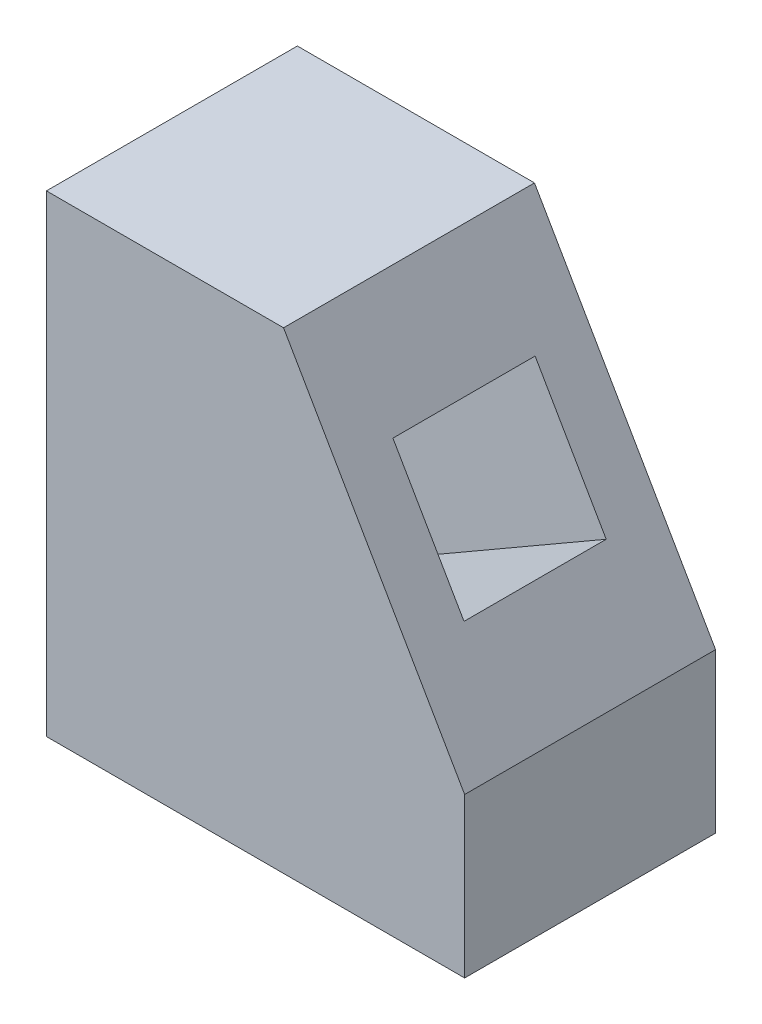
SolidWorks part; units mm, degrees
ref_plane "前视基准面" through (0, 0, 0) normal (0, 0, 1) x (1, 0, 0)
ref_plane "上视基准面" through (0, 0, 0) normal (0, 1, 0) x (1, 0, 0)
ref_plane "右视基准面" through (0, 0, 0) normal (1, 0, 0) x (0, 0, -1)
other "Configuration Table"
sketch "草图1" plane through (0, 0, 0) normal (0, 1, 0) x (1, 0, 0)
  line L0 (5, 0) -> (5, 6) construction
  line L1 (0, 0) -> (10, 0)
  line L2 (0, 0) -> (0, 6)
  line L3 (0, 6) -> (10, 6)
  line L4 (10, 0) -> (10, 6)
  dimension "D1" = 10
  dimension "D2" = 6
extrude "凸台-拉伸1" add sketch "草图1" along normal blind 11.3
sketch "草图2" plane through (0, 0, -6) normal (0, 0, -1) x (-1, 0, 0)
  line L0 (-10, 3.8) -> (-5.6699, 11.3)
  line L1 (-10, 11.3) -> (-10, 0) construction
  line L2 (-10, 11.3) -> (0, 11.3) construction
  line L3 (-5.6699, 11.3) -> (-10, 11.3)
  line L4 (-10, 11.3) -> (-10, 3.8)
  dimension "D1" = 30
  dimension "D2" = 7.5
extrude "切除-拉伸1" cut sketch "草图2" against normal up to next
sketch "草图3" plane through (9.1454, 5.2801, 0) normal (0.866, 0.5, 0) x (0, 0, -1)
  line L0 (0, 2.621) -> (6, 2.621) construction
  line L1 (0, 6.9512) -> (0, -1.7091) construction
  line L2 (6, -1.7091) -> (6, 6.9512) construction
  line L3 (3, 3.6037) -> (3, 7.0371) construction
  line L4 (4.7, 4.321) -> (1.3, 4.321)
  line L5 (1.3, 4.321) -> (1.3, 0.921)
  line L6 (4.7, 4.321) -> (4.7, 0.921)
  line L7 (4.7, 0.921) -> (1.3, 0.921)
  point P7 (3, 2.621)
  point P14 (3, 4.321)
  point P15 (4.7, 2.621)
  point P16 (1.3, 2.621)
  dimension "D1" = 1.7
  dimension "D2" = 1.7
extrude "切除-拉伸2" cut sketch "草图3" against normal blind 8
sketch "草图4" plane through (0, 0, 0) normal (0, -1, 0) x (1, 0, 0)
  line L0 (0, 0) -> (10, -6) construction
  circle A0 centre (5, -3) radius 0.5
  dimension "D1" = 1
extrude "切除-拉伸3" cut sketch "草图4" against normal blind 0.1
